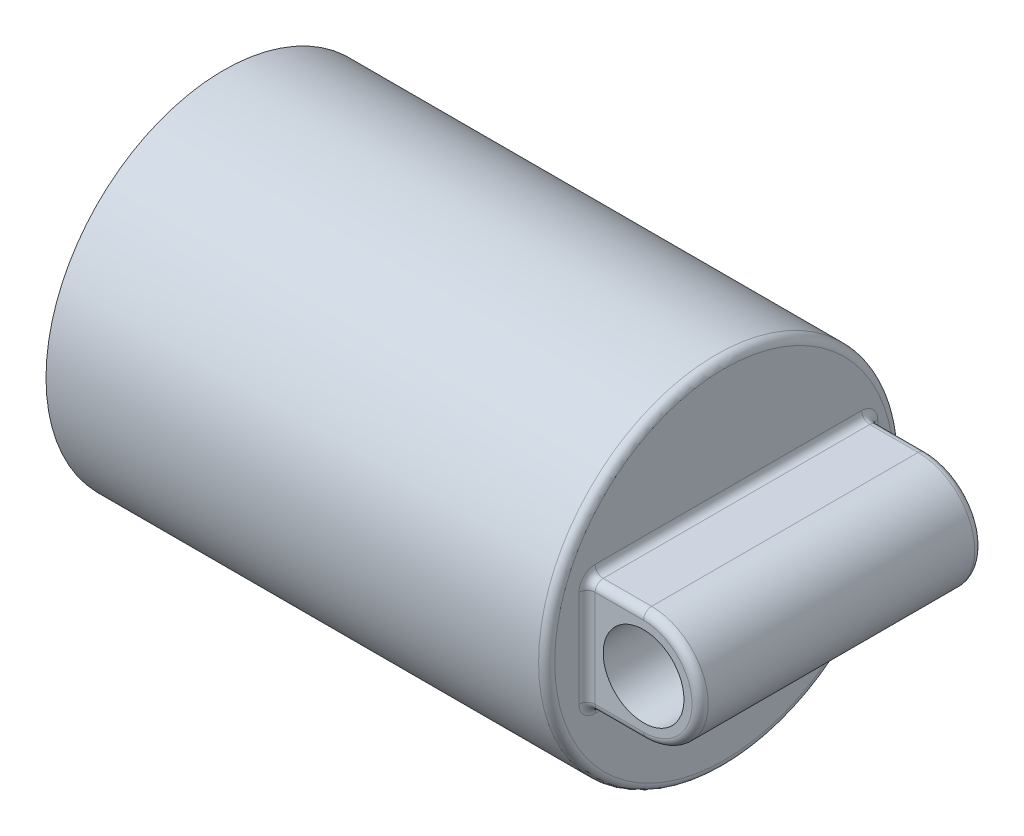
SolidWorks part; units mm, degrees
ref_plane "Front Plane" through (0, 0, 0) normal (0, 0, 1) x (1, 0, 0)
ref_plane "Top Plane" through (0, 0, 0) normal (0, 1, 0) x (1, 0, 0)
ref_plane "Right Plane" through (0, 0, 0) normal (1, 0, 0) x (0, 0, -1)
sketch "Sketch1" plane through (0, 0, 0) normal (0, 0, 1) x (1, 0, 0)
  line L0 (2, 22) -> (2, 0)
  line L1 (0, 0) -> (0, 20)
  line L2 (0, 20) -> (-60, 20)
  line L3 (-60, 20) -> (-60, 22)
  line L4 (-60, 22) -> (2, 22)
  line L5 (2, 0) -> (0, 0)
  line L6 (-25.9114, 0) -> (12.7205, 0) construction
  dimension "D1" = 2
  dimension "D2" = 2
  dimension "D3" = 20
  dimension "D4" = 60
revolve "Revolve1" add sketch "Sketch1" angle 360 about L6
ref_plane "Plane1" through (0, 0, 22) normal (0, 0, 1) x (1, 0, 0)
ref_plane "Plane2" through (0, 0, 17) normal (0, 0, 1) x (1, 0, 0)
sketch "Sketch3" plane through (0, 0, 17) normal (0, 0, 1) x (1, 0, 0)
  line L0 (2, -22) -> (2, 22) construction
  line L1 (0, 0) -> (9, 0) construction
  line L2 (9, 7) -> (2, 7)
  line L3 (2, 7) -> (2, -7)
  line L4 (2, -7) -> (9, -7)
  circle A0 centre (9, 0) radius 5
  arc A1 (9, -7) -> (9, 7) centre (9, 0) ccw
  dimension "D1" = 14
  dimension "D2" = 2
extrude "Boss-Extrude2" add sketch "Sketch3" against normal blind 35
fillet "Fillet2" radius 1 1 edges at (2, 0, 22)
fillet "Fillet3" radius 1 10 edges at (2, 0, 17) (2, -7, -0.5) (2, 7, -0.5) (5.5, -7, -18) (5.5, 7, -18) (5.5, -7, 17) (5.5, 7, 17) (2, 0, -18) (16, 0, -18) (16, 0, 17)
